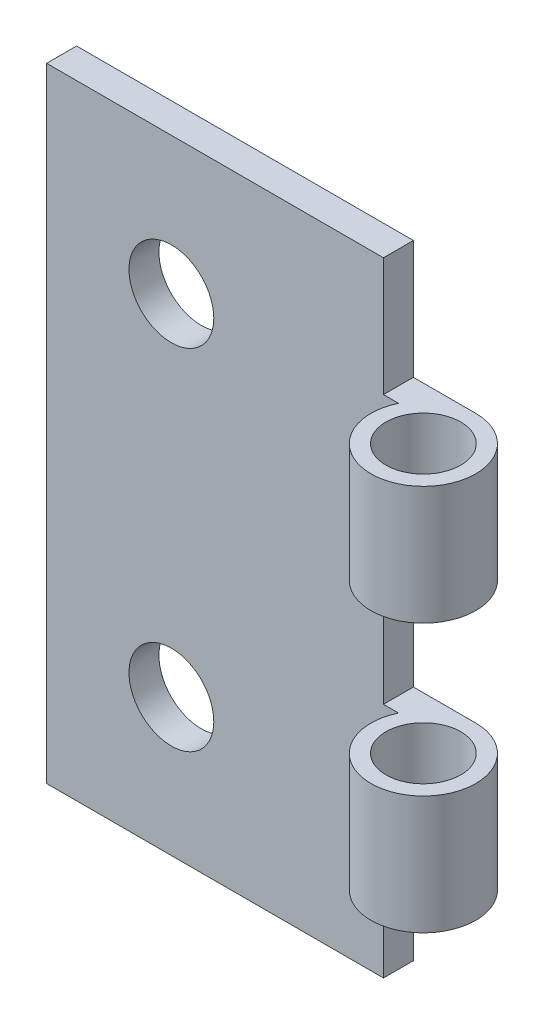
SolidWorks part; units mm, degrees
ref_plane "前视基准面" through (0, 0, 0) normal (0, 0, 1) x (1, 0, 0)
ref_plane "上视基准面" through (0, 0, 0) normal (0, 1, 0) x (1, 0, 0)
ref_plane "右视基准面" through (0, 0, 0) normal (1, 0, 0) x (0, 0, -1)
sketch "草图1" plane through (0, 0, 0) normal (0, 0, 1) x (1, 0, 0)
  line L0 (0, 0) -> (50000, 0) construction
  line L1 (6.75, -12.5) -> (-6.75, -12.5)
  line L2 (6.75, -12.5) -> (6.75, 12.5)
  line L3 (6.75, 12.5) -> (-6.75, 12.5)
  line L4 (-6.75, -12.5) -> (-6.75, 12.5)
  line L5 (6.75, -12.5) -> (-6.75, 12.5) construction
  line L6 (6.75, 12.5) -> (-6.75, -12.5) construction
  line L7 (6.75, 7.75) -> (9.25, 7.75)
  line L8 (6.75, 7.75) -> (6.75, 3)
  line L9 (6.75, 3) -> (9.25, 3)
  line L10 (9.25, 7.75) -> (9.25, 3)
  line L11 (6.75, -3) -> (9.25, -3)
  line L12 (6.75, -3) -> (6.75, -7.75)
  line L13 (6.75, -7.75) -> (9.25, -7.75)
  line L14 (9.25, -3) -> (9.25, -7.75)
  line L15 (-1.75, 7) -> (-1.75, -7) construction
  circle A0 centre (-1.75, 7) radius 1.7
  circle A1 centre (-1.75, -7) radius 1.7
  point P0 (0, 0)
  dimension "D7" = 3.4
  dimension "D9" = 8.5
  dimension "D1" = 25
  dimension "D2" = 13.5
  dimension "D3" = 2.5
  dimension "D4" = 4.75
  dimension "D5" = 4.75
  dimension "D6" = 4.75
  dimension "D8" = 14
extrude "凸台-拉伸1" add sketch "草图1" along normal blind 1.2 contours L4 L1 L2 L3 A1 A0 | L10 L7 L2 L9 | L14 L11 L2 L13
sketch "草图2" plane through (0, -7.75, 0) normal (0, -1, 0) x (1, 0, 0)
  line L0 (6.75, 0) -> (9.25, 0) construction
  line L3 (6.75, 1.2) -> (6.75, 0) construction
  circle A0 centre (9.25, 2.1) radius 2.1
  dimension "D2" = 4.2
  dimension "D3" = 2.5
extrude "凸台-拉伸2" add sketch "草图2" against normal blind 15.5
sketch "草图3" plane through (0, -7.75, 0) normal (0, -1, 0) x (1, 0, 0)
  circle A0 centre (9.25, 2.1) radius 1.5
  arc A1 (9.25, 0) -> (7.3526, 1.2) centre (9.25, 2.1) ccw construction
  dimension "D1" = 3
extrude "切除-拉伸1" cut sketch "草图3" against normal blind 18
sketch "草图4" plane through (0, 0, 1.2) normal (0, 0, 1) x (1, 0, 0)
  line L0 (6.75, -3) -> (7.3526, -3) construction
  line L1 (6.75, 3) -> (11.35, 3)
  line L2 (6.75, 3) -> (6.75, -3)
  line L3 (6.75, -3) -> (11.35, -3)
  line L4 (11.35, 3) -> (11.35, -3)
  line L5 (6.75, -3) -> (6.75, 3) construction
  line L6 (11.35, -7.75) -> (11.35, 7.75) construction
extrude "切除-拉伸2" cut sketch "草图4" against normal mid plane 10
